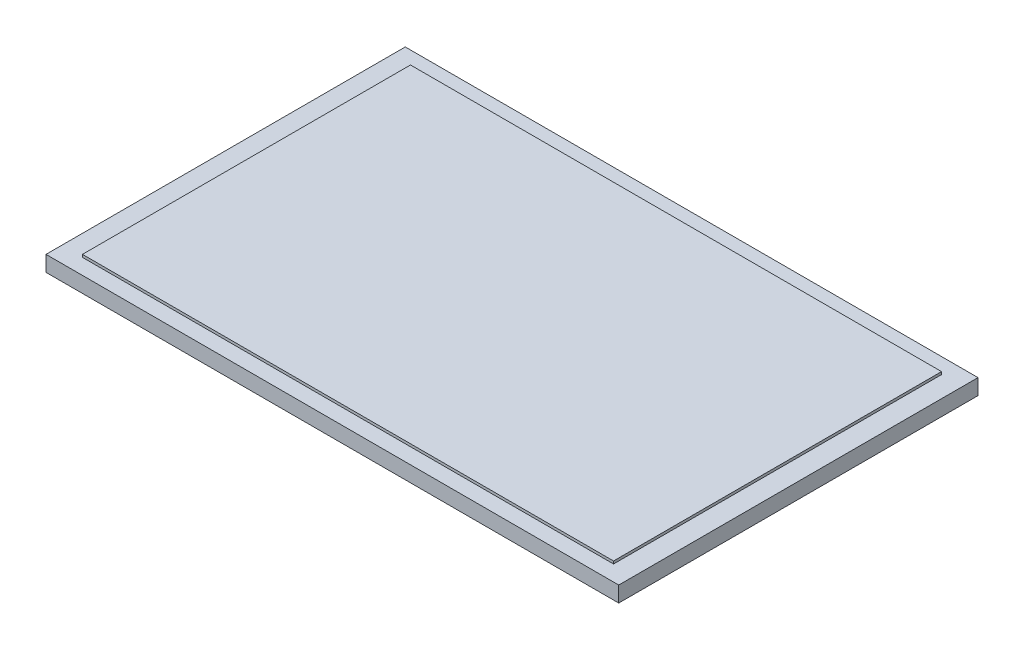
SolidWorks part; units mm, degrees
ref_plane "Front Plane" through (0, 0, 0) normal (0, 0, 1) x (1, 0, 0)
ref_plane "Top Plane" through (0, 0, 0) normal (0, 1, 0) x (1, 0, 0)
ref_plane "Right Plane" through (0, 0, 0) normal (1, 0, 0) x (0, 0, -1)
sketch "Sketch1" plane through (0, 0, 0) normal (0, 1, 0) x (1, 0, 0)
  line L1 (-55, -34.5) -> (55, -34.5)
  line L2 (-55, -34.5) -> (-55, 34.5)
  line L3 (-55, 34.5) -> (55, 34.5)
  line L4 (55, -34.5) -> (55, 34.5)
  line L5 (-55, -34.5) -> (55, 34.5) construction
  line L6 (-55, 34.5) -> (55, -34.5) construction
  point P0 (0, 0)
  dimension "D1" = 110
  dimension "D2" = 69
extrude "Boss-Extrude3" add sketch "Sketch1" along normal blind 3
sketch "Sketch2" plane through (0, 3, 0) normal (0, 1, 0) x (1, 0, 0)
  line L0 (55, -34.5) -> (55, 34.5) construction
  line L1 (-51, -31.5) -> (51, -31.5)
  line L2 (-51, -31.5) -> (-51, 31.5)
  line L3 (-51, 31.5) -> (51, 31.5)
  line L4 (51, -31.5) -> (51, 31.5)
  line L5 (-51, -31.5) -> (51, 31.5) construction
  line L6 (-51, 31.5) -> (51, -31.5) construction
  line L7 (55, 34.5) -> (-55, 34.5) construction
  point P0 (0, 0)
  dimension "D1" = 4
  dimension "D2" = 3
extrude "Boss-Extrude4" add sketch "Sketch2" along normal blind 0.5
